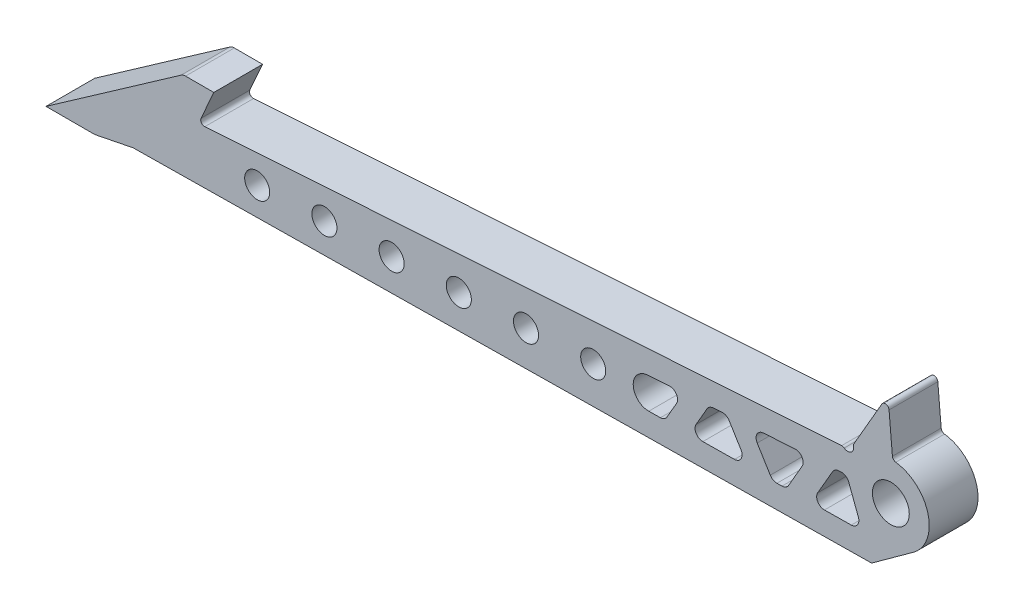
SolidWorks part; units mm, degrees
ref_plane "Front Plane" through (0, 0, 0) normal (0, 0, 1) x (1, 0, 0)
ref_plane "Top Plane" through (0, 0, 0) normal (0, 1, 0) x (1, 0, 0)
ref_plane "Right Plane" through (0, 0, 0) normal (1, 0, 0) x (0, 0, -1)
sketch "Sketch1" plane through (0, 0, 0) normal (0, 0, 1) x (1, 0, 0)
  line L0 (-184.1014, 66.7622) -> (-174.1014, 68.7622)
  line L1 (-184.1014, 66.7622) -> (-196.8014, 66.7622)
  line L2 (-196.8014, 66.7622) -> (-161.0977, 91.7622)
  line L3 (-161.0977, 91.7622) -> (-153.0977, 91.7622)
  line L4 (-153.0977, 91.7622) -> (-157.0977, 82.7622)
  line L5 (-40.1503, 84.4991) -> (11.7061, 87.9357)
  line L6 (-174.1014, 68.7622) -> (18.1986, 71.2622)
  line L7 (18.1986, 71.2622) -> (29.0674, 79.1405)
  line L8 (16.0571, 94.2372) -> (-157.0977, 82.7622)
  line L9 (12.5068, 94.0019) -> (22.4576, 111.2372)
  line L10 (11.7061, 87.9357) -> (15.7606, 77.231)
  line L11 (15.7606, 77.231) -> (-39.8338, 76.5082)
  line L12 (22.4576, 111.2372) -> (23.6835, 97.2254)
  line L13 (22.7176, 112.6875) -> (30.656, 126.4372) construction
  line L14 (84.9758, 66.7622) -> (-105.9511, 66.7622) construction
  line L15 (-141.8014, 76.479) -> (-124.3014, 77.1708)
  line L16 (-141.8014, 69.1821) -> (-141.8014, 83.7759) construction
  line L17 (-124.3014, 77.1708) -> (-106.8014, 77.8626)
  line L18 (-106.8014, 77.8626) -> (-89.3014, 78.5544)
  line L19 (-89.3014, 78.5544) -> (-71.8014, 79.2462)
  line L20 (-124.3014, 77.1708) -> (-106.8014, 77.8626)
  line L21 (-106.8014, 77.8626) -> (-89.3014, 78.5544)
  line L22 (-89.3014, 78.5544) -> (-71.8014, 79.2462)
  line L23 (-71.8014, 79.2462) -> (-54.3014, 79.938)
  circle A0 centre (23.1986, 87.2372) radius 10
  circle A1 centre (23.1986, 87.2372) radius 4.8025
  arc A2 (-39.8338, 76.5082) -> (-40.1503, 84.4991) centre (-39.8858, 80.5079) cw
  circle A3 centre (-141.8014, 76.479) radius 3.2639
  circle A4 centre (-106.8014, 77.8626) radius 3.2639
  circle A5 centre (-71.8014, 79.2462) radius 3.2639
  circle A6 centre (-124.3014, 77.1708) radius 3.2639
  circle A7 centre (-89.3014, 78.5544) radius 3.2639
  circle A8 centre (-54.3014, 79.938) radius 3.2639
  point P33 (-141.8014, 76.479)
  dimension "D1" = 20
  dimension "D19" = 4
  dimension "D20" = 6.5278
  dimension "D28" = 9.605
  dimension "D2" = 12.7
  dimension "D3" = 35
  dimension "D4" = 220
  dimension "D5" = 8
  dimension "D6" = 2
  dimension "D7" = 25
  dimension "D8" = 4
  dimension "D9" = 14
  dimension "D10" = 5
  dimension "D11" = 6
  dimension "D12" = 6
  dimension "D13" = 70
  dimension "D14" = 10.5
  dimension "D15" = 1
  dimension "D16" = 10
  dimension "D17" = 35
  dimension "D18" = 24
  dimension "D21" = 55
  dimension "D22" = 125
  dimension "D23" = 4.5
  dimension "D24" = 7
  dimension "D25" = 66.7622
  dimension "D26" = 87.2372
  dimension "D27" = 23.1986
extrude "Boss-Extrude1" add sketch "Sketch1" along normal blind 12.7
sketch "Sketch2" plane through (0, 0, 12.7) normal (0, 0, 1) x (1, 0, 0)
  line L0 (12.5068, 94.0019) -> (11.9785, 94.8509) construction
  line L1 (12.5068, 94.0019) -> (-157.0977, 82.7622) construction
  line L2 (12.5068, 94.0019) -> (22.4576, 111.2372) construction
  line L3 (12.5068, 94.0019) -> (-157.0977, 82.7622) construction
  line L4 (12.5068, 94.0019) -> (22.4576, 111.2372) construction
  circle A0 centre (11.9785, 94.8509) radius 1.5
  dimension "D2" = 3
  dimension "D1" = 1
  dimension "D3" = 123.791
  dimension "D4" = 61.896
extrude "Cut-Extrude1" cut sketch "Sketch2" against normal through all
sketch "Sketch3" plane through (0, 0, 12.7) normal (0, 0, 1) x (1, 0, 0)
  line L0 (5.2565, 87.5083) -> (-0.8014, 77.0157)
  line L1 (-10.8006, 76.8857) -> (-16.4262, 86.0713)
  line L2 (-10.8006, 76.8857) -> (-8.7115, 73.4746)
  line L3 (-0.8014, 77.0157) -> (-2.3014, 74.4176)
  line L4 (5.2565, 87.5083) -> (6.7565, 90.1063)
  line L5 (-16.4262, 86.0713) -> (-18.5153, 89.4825)
  line L6 (-27.4262, 85.3424) -> (-32.4714, 76.604)
  line L7 (-32.4714, 76.604) -> (-33.9714, 74.0059)
  line L8 (-27.4262, 85.3424) -> (-25.9262, 87.9405)
  line L9 (-5.801, 76.9507) -> (-6.1807, 106.1593) construction
  line L10 (15.7606, 77.231) -> (-39.8338, 76.5082) construction
  line L11 (-40.1503, 84.4991) -> (11.7061, 87.9357) construction
  circle A0 centre (23.1986, 87.2372) radius 4.8025 construction
  dimension "D1" = 24
  dimension "D2" = 3
  dimension "D3" = 4
  dimension "D4" = 3
  dimension "D5" = 30.74
  dimension "D6" = 5
  dimension "D7" = 11
  dimension "D8" = 11.1938
extrude "Extrude-Thin1" add sketch "Sketch3" against normal up to surface (12.7 mm away) thin up to face at (-51.0375, 79.938, 0) thin type mid plane wall 5.5
fillet "Fillet1" radius 2 14 edges at (-13.3272, 86.2767, 6.35) (1.9547, 87.2895, 6.35) (-24.1245, 85.5612, 6.35) (-19.5252, 85.866, 6.35) (-30.728, 85.1236, 6.35) (8.5582, 87.7271, 6.35) (11.7061, 87.9357, 6.35) (-7.6013, 76.9273, 6.35) (-4.0009, 76.9741, 6.35) (-29.2719, 76.6456, 6.35) (-13.9999, 76.8441, 6.35) (-35.6708, 76.5624, 6.35) (2.398, 77.0573, 6.35) (15.7606, 77.231, 6.35)
fillet "Fillet2" radius 1 2 edges at (10.8262, 93.8905, 6.35) (13.349, 95.4606, 6.35)
fillet "Fillet3" radius 1 1 edges at (-157.0977, 82.7622, 6.35)
fillet "Fillet4" radius 2 1 edges at (-161.0977, 91.7622, 6.35)
fillet "Fillet5" radius 1 2 edges at (23.6835, 97.2254, 6.35) (22.4576, 111.2372, 6.35)
equation "\"D4@Sketch2\"=\"D3@Sketch2\"/2"
